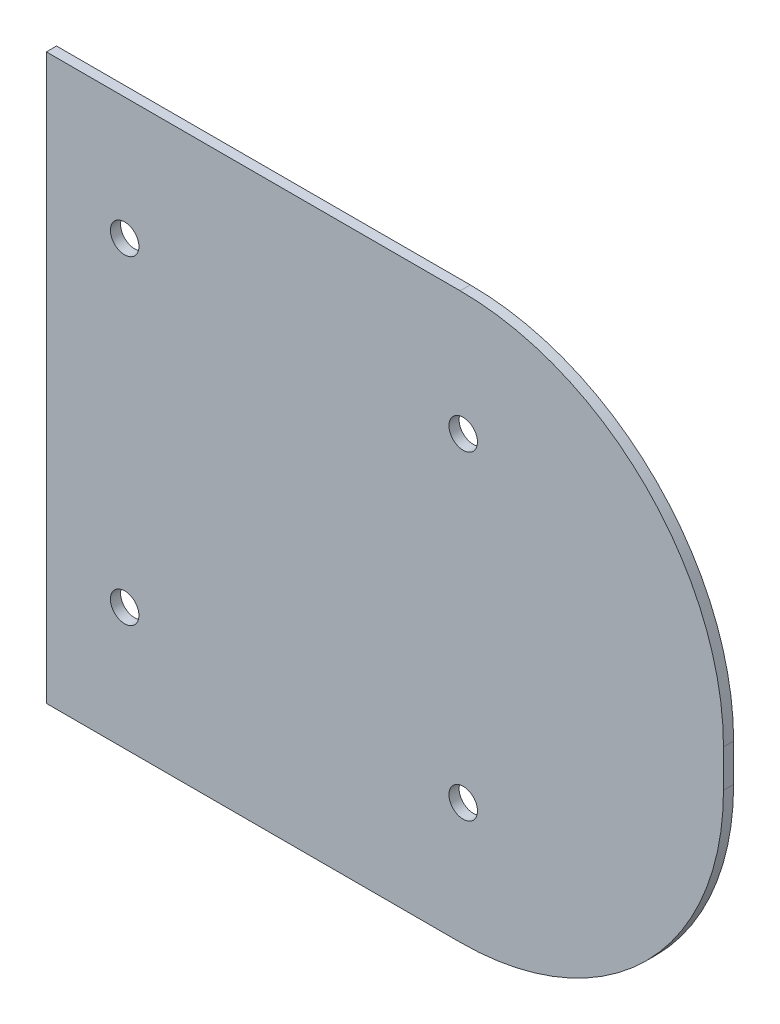
SolidWorks part; units mm, degrees
ref_plane "Ön Düzlem" through (0, 0, 0) normal (0, 0, 1) x (1, 0, 0)
ref_plane "Üst Düzlem" through (0, 0, 0) normal (0, 1, 0) x (1, 0, 0)
ref_plane "Sağ Düzlem" through (0, 0, 0) normal (1, 0, 0) x (0, 0, -1)
sketch "Çizim1" plane through (0, 0, 0) normal (0, 0, 1) x (1, 0, 0)
  line L1 (-90, -75) -> (20, -75)
  line L2 (-90, -75) -> (-90, 75)
  line L3 (-90, 75) -> (20, 75)
  line L4 (90, -5) -> (90, 5)
  line L5 (-90, -75) -> (90, 75) construction
  line L6 (-90, 75) -> (90, -75) construction
  arc A0 (20, 75) -> (90, 5) centre (20, 5) cw
  arc A1 (20, -75) -> (90, -5) centre (20, -5) ccw
  point P0 (0, 0)
  dimension "D3" = 70
  dimension "D4" = 70
  dimension "D1" = 150
  dimension "D2" = 180
extrude "Yükseklik-Ekstrüzyon3" add sketch "Çizim1" along normal blind 2.7
sketch "Çizim2" plane through (0, 0, 2.7) normal (0, 0, 1) x (1, 0, 0)
  line L0 (0, 0) -> (50000, 0) construction
  circle A0 centre (-69.1872, 42.4686) radius 3.79
  circle A1 centre (20.8128, 42.4686) radius 3.79
  circle A2 centre (20.8128, -42.4686) radius 3.79
  circle A3 centre (-69.1872, -42.4686) radius 3.79
  dimension "D1" = 2
  dimension "D2" = 7.58
extrude "Kes-Ekstrüzyon1" cut sketch "Çizim2" against normal blind 2.75
